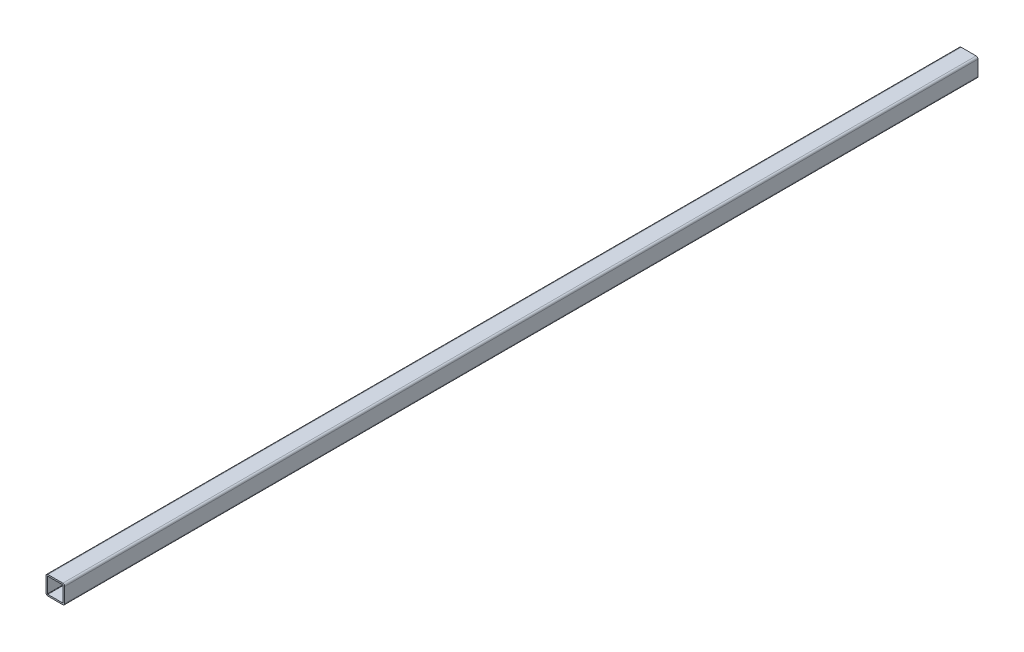
SolidWorks part; units mm, degrees
ref_plane "Front Plane" through (0, 0, 0) normal (0, 0, 1) x (1, 0, 0)
ref_plane "Top Plane" through (0, 0, 0) normal (0, 1, 0) x (1, 0, 0)
ref_plane "Right Plane" through (0, 0, 0) normal (1, 0, 0) x (0, 0, -1)
sketch "Sketch1" plane through (0, 0, 0) normal (0, 0, 1) x (1, 0, 0)
  line L1 (10, -12.5) -> (-10, -12.5)
  line L2 (12.5, -10) -> (12.5, 10)
  line L3 (10, 12.5) -> (-10, 12.5)
  line L4 (-12.5, -10) -> (-12.5, 10)
  line L5 (12.5, -12.5) -> (-12.5, 12.5) construction
  line L6 (12.5, 12.5) -> (-12.5, -12.5) construction
  arc A0 (-10, 12.5) -> (-12.5, 10) centre (-10, 10) ccw
  arc A1 (12.5, 10) -> (10, 12.5) centre (10, 10) ccw
  arc A2 (10, -12.5) -> (12.5, -10) centre (10, -10) ccw
  arc A3 (-10, -12.5) -> (-12.5, -10) centre (-10, -10) cw
  point P0 (0, 0)
  dimension "D2" = 2.5
  dimension "D1" = 25
extrude "Extrude-Thin1" add sketch "Sketch1" along normal mid plane 1219.2 thin
equation "\"D2@Sketch1\" = \"D5@Extrude-Thin1\" * 1.25"
